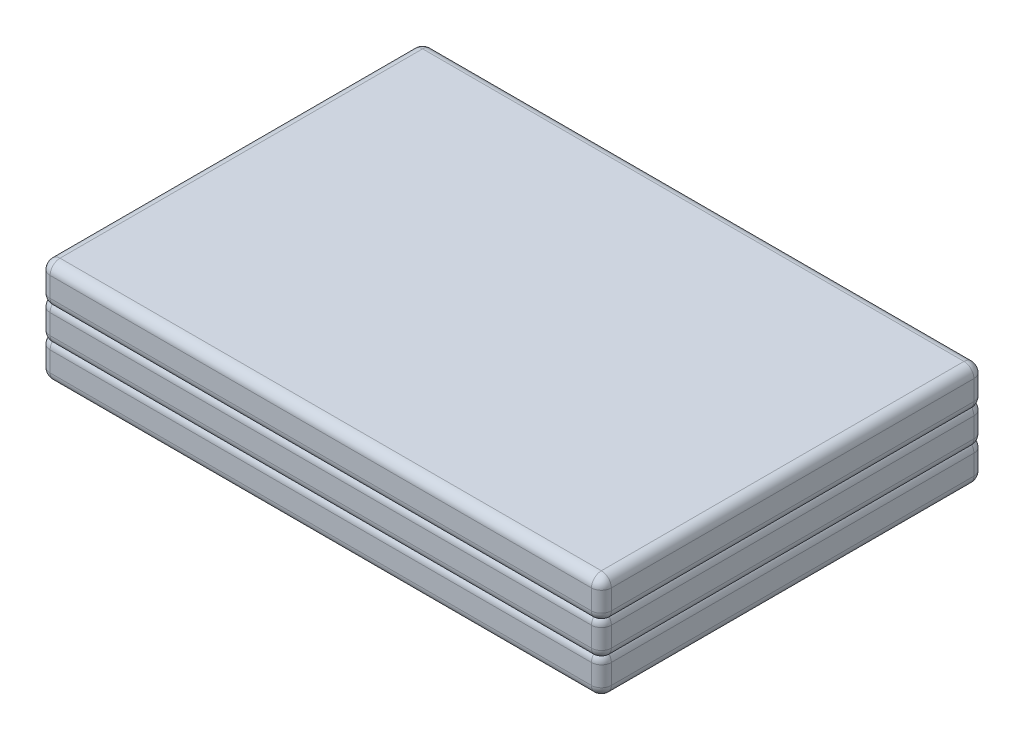
SolidWorks part; units mm, degrees
ref_plane "Front Plane" through (0, 0, 0) normal (0, 0, 1) x (1, 0, 0)
ref_plane "Top Plane" through (0, 0, 0) normal (0, 1, 0) x (1, 0, 0)
ref_plane "Right Plane" through (0, 0, 0) normal (1, 0, 0) x (0, 0, -1)
sketch "Sketch1" plane through (0, 0, 0) normal (0, 1, 0) x (1, 0, 0)
  line L1 (56.5, -38.5) -> (-56.5, -38.5)
  line L2 (56.5, -38.5) -> (56.5, 38.5)
  line L3 (56.5, 38.5) -> (-56.5, 38.5)
  line L4 (-56.5, -38.5) -> (-56.5, 38.5)
  line L5 (56.5, -38.5) -> (-56.5, 38.5) construction
  line L6 (56.5, 38.5) -> (-56.5, -38.5) construction
  point P0 (0, 0)
  dimension "D1" = 113
  dimension "D2" = 77
extrude "Boss-Extrude1" add sketch "Sketch1" along normal blind 8
fillet "Fillet1" radius 2 12 edges at (56.5, 8, 0) (-56.5, 8, 0) (56.5, 4, -38.5) (0, 8, -38.5) (-56.5, 4, -38.5) (-56.5, 4, 38.5) (0, 8, 38.5) (56.5, 4, 38.5) (0, 0, 38.5) (56.5, 0, 0) (0, 0, -38.5) (-56.5, 0, 0)
pattern_linear "LPattern3" count 3 spacing 6.5 along (0, 1, 0) of bodies 101
combine bodies "Combine1" operation type add bodies to combine 101 104 103
